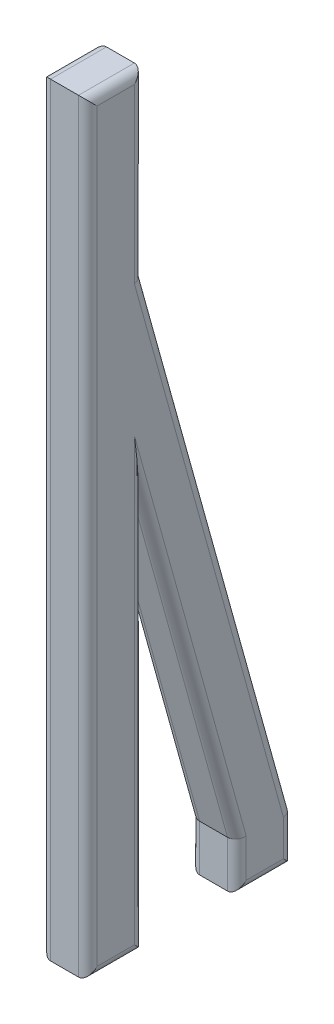
SolidWorks part; units mm, degrees
material "ABS"
ref_plane "Front Plane" through (0, 0, 0) normal (0, 0, 1) x (1, 0, 0)
ref_plane "Top Plane" through (0, 0, 0) normal (0, 1, 0) x (1, 0, 0)
ref_plane "Right Plane" through (0, 0, 0) normal (1, 0, 0) x (0, 0, -1)
sketch "Sketch1" plane through (0, 0, 0) normal (1, 0, 0) x (0, 0, -1)
  line L0 (6, -72) -> (-6, -72) construction
  line L1 (-6, 82) -> (6, 82)
  line L2 (-6, 82) -> (-6, -82)
  line L3 (-6, -82) -> (6, -82)
  line L4 (6, 82) -> (6, -82)
  line L5 (-6, 82) -> (6, -82) construction
  line L6 (-6, -82) -> (6, 82) construction
  line L7 (-60.6379, -98) -> (88.7697, -98) construction
  line L8 (6, 43.2) -> (38, -72)
  line L9 (38, -72) -> (38, -82)
  line L10 (38, -82) -> (26, -82)
  line L11 (26, -82) -> (26, -72)
  line L12 (26, -72) -> (6, 0)
  line L13 (6, 0) -> (6, 43.2)
  point P0 (0, 0)
  point P16 (6, 14.0695)
  point P17 (6, 0)
  point P18 (6, 0)
  dimension "D1" = 12
  dimension "D2" = 10
  dimension "D3" = 26
  dimension "D4" = 180
  dimension "D5" = 20
extrude "Boss-Extrude1" add sketch "Sketch1" along normal mid plane 10 contours L12 L11 L10 L9 L8 L4 | L4 L1 L2 L3
fillet "Fillet1" radius 2 20 edges at (-5, -77, -26) (-5, -82, -32) (-5, -77, -38) (-5, -14.4, -22) (-5, 62.6, -6) (-5, 82, 0) (-5, 0, 6) (-5, -82, 0) (-5, -41, -6) (-5, -36, -16) (5, -41, -6) (5, -82, 0) (5, 0, 6) (5, 82, 0) (5, 62.6, -6) (5, -14.4, -22) (5, -77, -38) (5, -82, -32) (5, -77, -26) (5, -36, -16)
